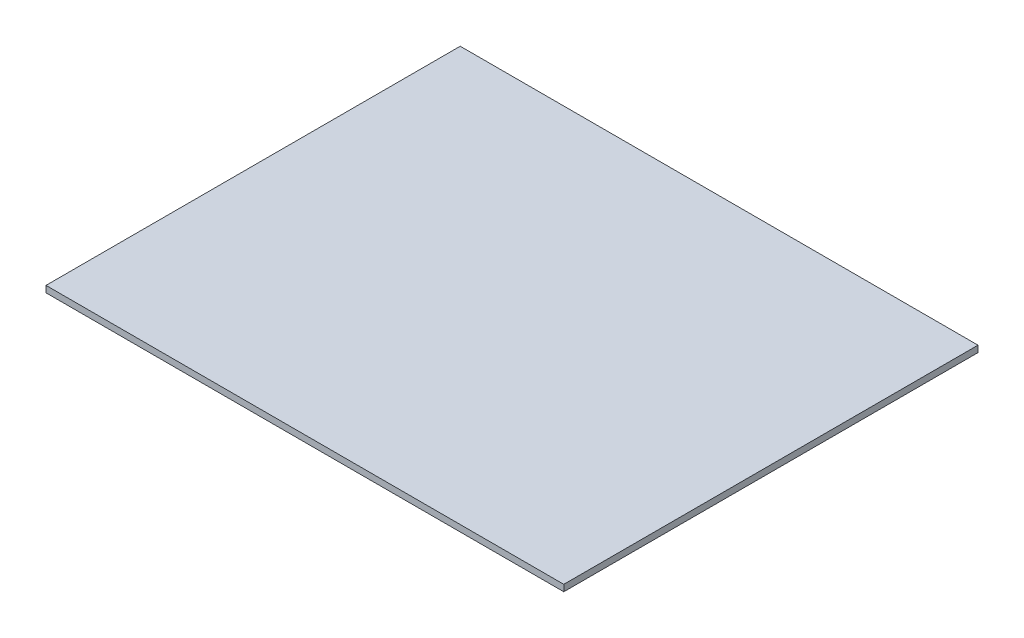
SolidWorks part; units mm, degrees
ref_plane "Front Plane" through (0, 0, 0) normal (0, 0, 1) x (1, 0, 0)
ref_plane "Top Plane" through (0, 0, 0) normal (0, 1, 0) x (1, 0, 0)
ref_plane "Right Plane" through (0, 0, 0) normal (1, 0, 0) x (0, 0, -1)
sketch "Sketch2" plane through (0, 0, 0) normal (0, 1, 0) x (1, 0, 0)
  line L1 (-381, 304.8) -> (381, 304.8)
  line L2 (-381, 304.8) -> (-381, -304.8)
  line L3 (-381, -304.8) -> (381, -304.8)
  line L4 (381, 304.8) -> (381, -304.8)
  line L5 (-381, 304.8) -> (381, -304.8) construction
  line L6 (-381, -304.8) -> (381, 304.8) construction
  point P0 (0, 0)
  dimension "D1" = 762
  dimension "D2" = 609.6
extrude "Boss-Extrude1" add sketch "Sketch2" along normal blind 9.525
